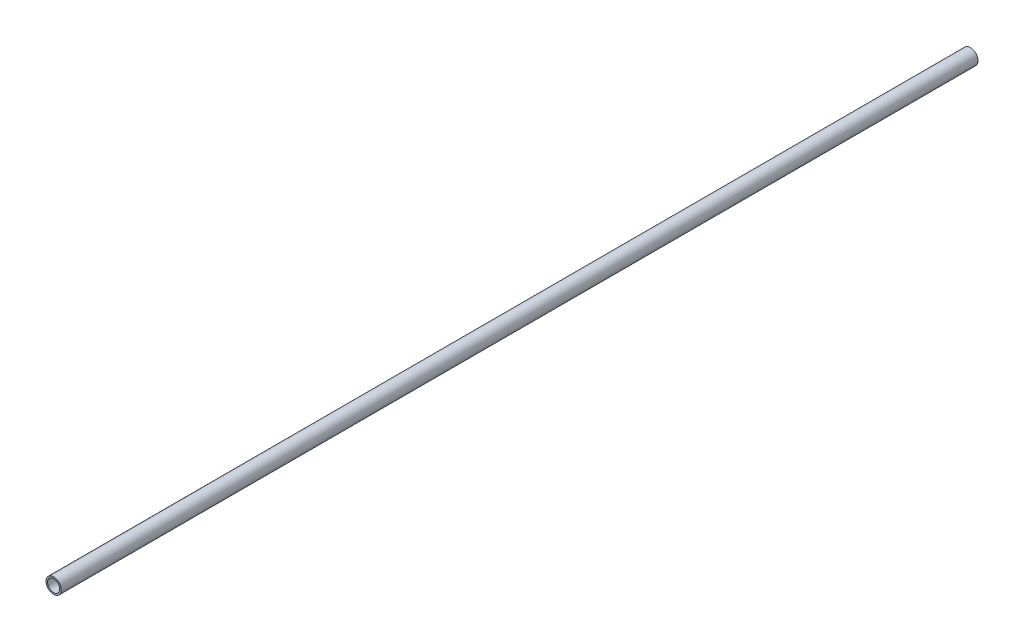
SolidWorks part; units mm, degrees
material "1060 Alloy"
ref_plane "Front Plane" through (0, 0, 0) normal (0, 0, 1) x (1, 0, 0)
ref_plane "Top Plane" through (0, 0, 0) normal (0, 1, 0) x (1, 0, 0)
ref_plane "Right Plane" through (0, 0, 0) normal (1, 0, 0) x (0, 0, -1)
sketch "Sketch1" plane through (0, 0, 0) normal (0, 0, 1) x (1, 0, 0)
  circle A0 centre (0, 0) radius 5
  circle A1 centre (0, 0) radius 4
  dimension "D1" = 8
  dimension "D2" = 10
extrude "Boss-Extrude1" add sketch "Sketch1" along normal blind 600 contours A0 A1
